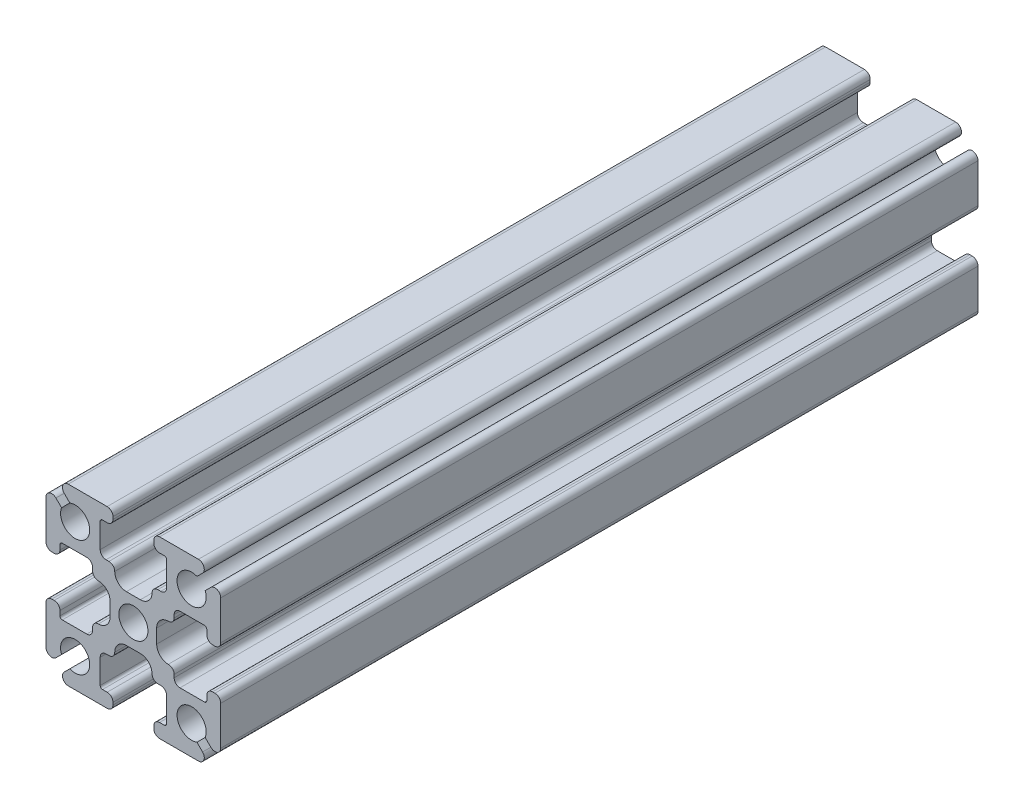
SolidWorks part; units mm, degrees
ref_plane "Front" through (0, 0, 0) normal (0, 0, 1) x (1, 0, 0)
ref_plane "Top" through (0, 0, 0) normal (0, 1, 0) x (1, 0, 0)
ref_plane "Right" through (0, 0, 0) normal (1, 0, 0) x (0, 0, -1)
sketch "Sketch1" plane through (0, 0, 0) normal (0, 0, 1) x (1, 0, 0)
  line L0 (6.6464, 5.9393) -> (6.1636, 5.4565)
  line L1 (5.4565, 6.1636) -> (5.9393, 6.6464)
  line L2 (5.5858, 7.5) -> (2.25, 7.5)
  line L3 (1.75, 7) -> (1.75, 6.8)
  line L4 (2.25, 6.3) -> (2.65, 6.3)
  line L5 (2.85, 6.1) -> (2.85, 4)
  line L6 (2.35, 3.5) -> (2.1, 3.5)
  line L7 (0.6, 2) -> (-0.6, 2)
  line L8 (-2.1, 3.5) -> (-2.35, 3.5)
  line L9 (-2.85, 4) -> (-2.85, 6.1)
  line L10 (-2.65, 6.3) -> (-2.25, 6.3)
  line L11 (-1.75, 6.8) -> (-1.75, 7)
  line L12 (-2.25, 7.5) -> (-5.5858, 7.5)
  line L13 (-5.9393, 6.6464) -> (-5.4565, 6.1636)
  line L14 (-6.1636, 5.4565) -> (-6.6464, 5.9393)
  line L15 (-7.5, 5.5858) -> (-7.5, 2.25)
  line L16 (-7, 1.75) -> (-6.8, 1.75)
  line L17 (-6.3, 2.25) -> (-6.3, 2.65)
  line L18 (-6.1, 2.85) -> (-4, 2.85)
  line L19 (-3.5, 2.35) -> (-3.5, 2.1)
  line L20 (-2, 0.6) -> (-2, -0.6)
  line L21 (-3.5, -2.1) -> (-3.5, -2.35)
  line L22 (-4, -2.85) -> (-6.1, -2.85)
  line L23 (-6.3, -2.65) -> (-6.3, -2.25)
  line L24 (-6.8, -1.75) -> (-7, -1.75)
  line L25 (-7.5, -2.25) -> (-7.5, -5.5858)
  line L26 (-6.6464, -5.9393) -> (-6.1636, -5.4565)
  line L27 (-5.4565, -6.1636) -> (-5.9393, -6.6464)
  line L28 (-5.5858, -7.5) -> (-2.25, -7.5)
  line L29 (-1.75, -7) -> (-1.75, -6.8)
  line L30 (-2.25, -6.3) -> (-2.65, -6.3)
  line L31 (-2.85, -6.1) -> (-2.85, -4)
  line L32 (-2.35, -3.5) -> (-2.1, -3.5)
  line L33 (-0.6, -2) -> (0.6, -2)
  line L34 (2.1, -3.5) -> (2.35, -3.5)
  line L35 (2.85, -4) -> (2.85, -6.1)
  line L36 (2.65, -6.3) -> (2.25, -6.3)
  line L37 (1.75, -6.8) -> (1.75, -7)
  line L38 (2.25, -7.5) -> (5.5858, -7.5)
  line L39 (5.9393, -6.6464) -> (5.4565, -6.1636)
  line L40 (6.1636, -5.4565) -> (6.6464, -5.9393)
  line L41 (7.5, -5.5858) -> (7.5, -2.25)
  line L42 (7, -1.75) -> (6.8, -1.75)
  line L43 (6.3, -2.25) -> (6.3, -2.65)
  line L44 (6.1, -2.85) -> (4, -2.85)
  line L45 (3.5, -2.35) -> (3.5, -2.1)
  line L46 (2, -0.6) -> (2, 0.6)
  line L47 (3.5, 2.1) -> (3.5, 2.35)
  line L48 (4, 2.85) -> (6.1, 2.85)
  line L49 (6.3, 2.65) -> (6.3, 2.25)
  line L50 (6.8, 1.75) -> (7, 1.75)
  line L51 (7.5, 2.25) -> (7.5, 5.5858)
  circle A0 centre (0, 0) radius 1.25
  arc A1 (6.1636, 5.4565) -> (5.4565, 6.1636) centre (5, 5) cw
  arc A2 (5.9393, 6.6464) -> (5.5858, 7.5) centre (5.5858, 7) ccw
  arc A3 (2.25, 7.5) -> (1.75, 7) centre (2.25, 7) ccw
  arc A4 (1.75, 6.8) -> (2.25, 6.3) centre (2.25, 6.8) ccw
  arc A5 (2.65, 6.3) -> (2.85, 6.1) centre (2.65, 6.1) cw
  arc A6 (2.85, 4) -> (2.35, 3.5) centre (2.35, 4) cw
  arc A7 (2.1, 3.5) -> (1.6, 3) centre (2.1, 3) ccw
  arc A8 (1.6, 3) -> (0.6, 2) centre (0.6, 3) cw
  arc A9 (-0.6, 2) -> (-1.6, 3) centre (-0.6, 3) cw
  arc A10 (-1.6, 3) -> (-2.1, 3.5) centre (-2.1, 3) ccw
  arc A11 (-2.35, 3.5) -> (-2.85, 4) centre (-2.35, 4) cw
  arc A12 (-2.85, 6.1) -> (-2.65, 6.3) centre (-2.65, 6.1) cw
  arc A13 (-2.25, 6.3) -> (-1.75, 6.8) centre (-2.25, 6.8) ccw
  arc A14 (-1.75, 7) -> (-2.25, 7.5) centre (-2.25, 7) ccw
  arc A15 (-5.5858, 7.5) -> (-5.9393, 6.6464) centre (-5.5858, 7) ccw
  arc A16 (-5.4565, 6.1636) -> (-6.1636, 5.4565) centre (-5, 5) cw
  arc A17 (-6.6464, 5.9393) -> (-7.5, 5.5858) centre (-7, 5.5858) ccw
  arc A18 (-7.5, 2.25) -> (-7, 1.75) centre (-7, 2.25) ccw
  arc A19 (-6.8, 1.75) -> (-6.3, 2.25) centre (-6.8, 2.25) ccw
  arc A20 (-6.3, 2.65) -> (-6.1, 2.85) centre (-6.1, 2.65) cw
  arc A21 (-4, 2.85) -> (-3.5, 2.35) centre (-4, 2.35) cw
  arc A22 (-3.5, 2.1) -> (-3, 1.6) centre (-3, 2.1) ccw
  arc A23 (-3, 1.6) -> (-2, 0.6) centre (-3, 0.6) cw
  arc A24 (-2, -0.6) -> (-3, -1.6) centre (-3, -0.6) cw
  arc A25 (-3, -1.6) -> (-3.5, -2.1) centre (-3, -2.1) ccw
  arc A26 (-3.5, -2.35) -> (-4, -2.85) centre (-4, -2.35) cw
  arc A27 (-6.1, -2.85) -> (-6.3, -2.65) centre (-6.1, -2.65) cw
  arc A28 (-6.3, -2.25) -> (-6.8, -1.75) centre (-6.8, -2.25) ccw
  arc A29 (-7, -1.75) -> (-7.5, -2.25) centre (-7, -2.25) ccw
  arc A30 (-7.5, -5.5858) -> (-6.6464, -5.9393) centre (-7, -5.5858) ccw
  arc A31 (-6.1636, -5.4565) -> (-5.4565, -6.1636) centre (-5, -5) cw
  arc A32 (-5.9393, -6.6464) -> (-5.5858, -7.5) centre (-5.5858, -7) ccw
  arc A33 (-2.25, -7.5) -> (-1.75, -7) centre (-2.25, -7) ccw
  arc A34 (-1.75, -6.8) -> (-2.25, -6.3) centre (-2.25, -6.8) ccw
  arc A35 (-2.65, -6.3) -> (-2.85, -6.1) centre (-2.65, -6.1) cw
  arc A36 (-2.85, -4) -> (-2.35, -3.5) centre (-2.35, -4) cw
  arc A37 (-2.1, -3.5) -> (-1.6, -3) centre (-2.1, -3) ccw
  arc A38 (-1.6, -3) -> (-0.6, -2) centre (-0.6, -3) cw
  arc A39 (0.6, -2) -> (1.6, -3) centre (0.6, -3) cw
  arc A40 (1.6, -3) -> (2.1, -3.5) centre (2.1, -3) ccw
  arc A41 (2.35, -3.5) -> (2.85, -4) centre (2.35, -4) cw
  arc A42 (2.85, -6.1) -> (2.65, -6.3) centre (2.65, -6.1) cw
  arc A43 (2.25, -6.3) -> (1.75, -6.8) centre (2.25, -6.8) ccw
  arc A44 (1.75, -7) -> (2.25, -7.5) centre (2.25, -7) ccw
  arc A45 (5.5858, -7.5) -> (5.9393, -6.6464) centre (5.5858, -7) ccw
  arc A46 (5.4565, -6.1636) -> (6.1636, -5.4565) centre (5, -5) cw
  arc A47 (6.6464, -5.9393) -> (7.5, -5.5858) centre (7, -5.5858) ccw
  arc A48 (7.5, -2.25) -> (7, -1.75) centre (7, -2.25) ccw
  arc A49 (6.8, -1.75) -> (6.3, -2.25) centre (6.8, -2.25) ccw
  arc A50 (6.3, -2.65) -> (6.1, -2.85) centre (6.1, -2.65) cw
  arc A51 (4, -2.85) -> (3.5, -2.35) centre (4, -2.35) cw
  arc A52 (3.5, -2.1) -> (3, -1.6) centre (3, -2.1) ccw
  arc A53 (3, -1.6) -> (2, -0.6) centre (3, -0.6) cw
  arc A54 (2, 0.6) -> (3, 1.6) centre (3, 0.6) cw
  arc A55 (3, 1.6) -> (3.5, 2.1) centre (3, 2.1) ccw
  arc A56 (3.5, 2.35) -> (4, 2.85) centre (4, 2.35) cw
  arc A57 (6.1, 2.85) -> (6.3, 2.65) centre (6.1, 2.65) cw
  arc A58 (6.3, 2.25) -> (6.8, 1.75) centre (6.8, 2.25) ccw
  arc A59 (7, 1.75) -> (7.5, 2.25) centre (7, 2.25) ccw
  arc A60 (7.5, 5.5858) -> (6.6464, 5.9393) centre (7, 5.5858) ccw
extrude "Boss-Extrude1" add sketch "Sketch1" along normal blind 65
